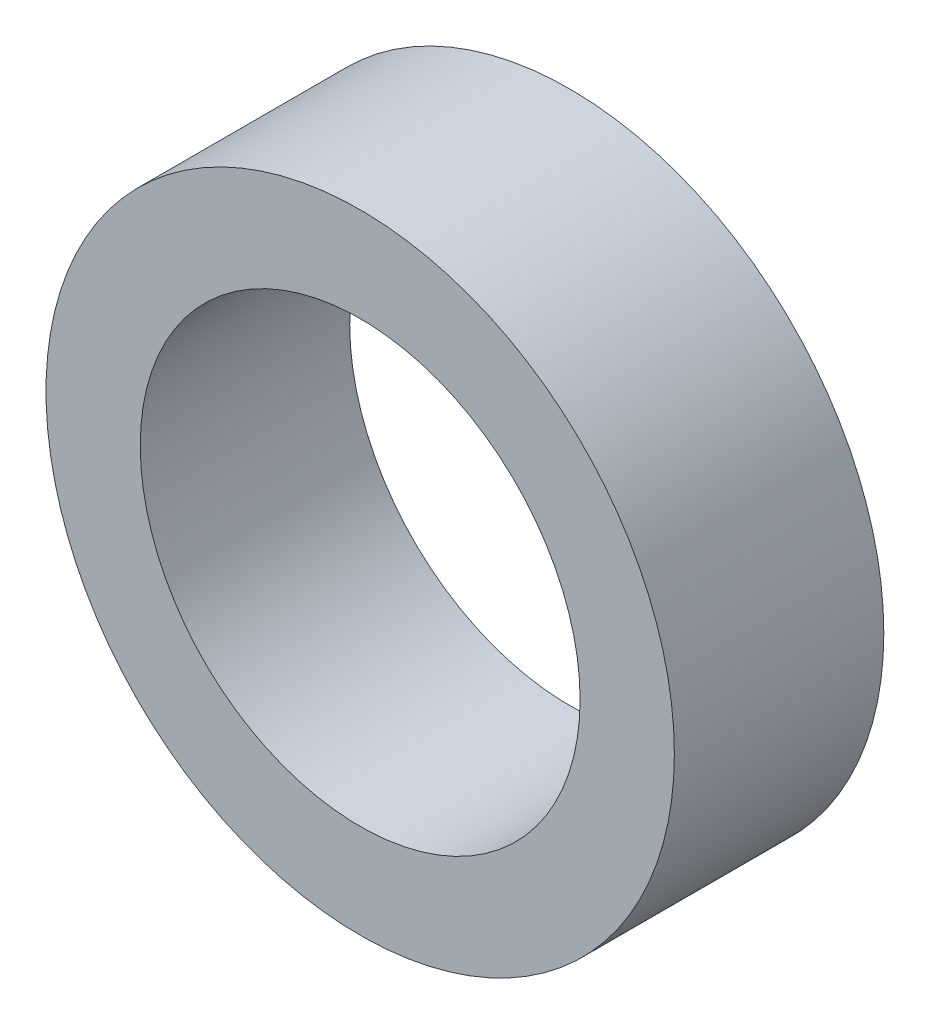
SolidWorks part; units mm, degrees
material "ABS"
ref_plane "前视基准面" through (0, 0, 0) normal (0, 0, 1) x (1, 0, 0)
ref_plane "上视基准面" through (0, 0, 0) normal (0, 1, 0) x (1, 0, 0)
ref_plane "右视基准面" through (0, 0, 0) normal (1, 0, 0) x (0, 0, -1)
sketch "草图1" plane through (0, 0, 0) normal (0, 0, 1) x (1, 0, 0)
  circle A0 centre (0, 0) radius 3
  circle A1 centre (0, 0) radius 2.1
  dimension "D1" = 4.2
  dimension "D2" = 6
extrude "凸台-拉伸1" add sketch "草图1" along normal blind 2
